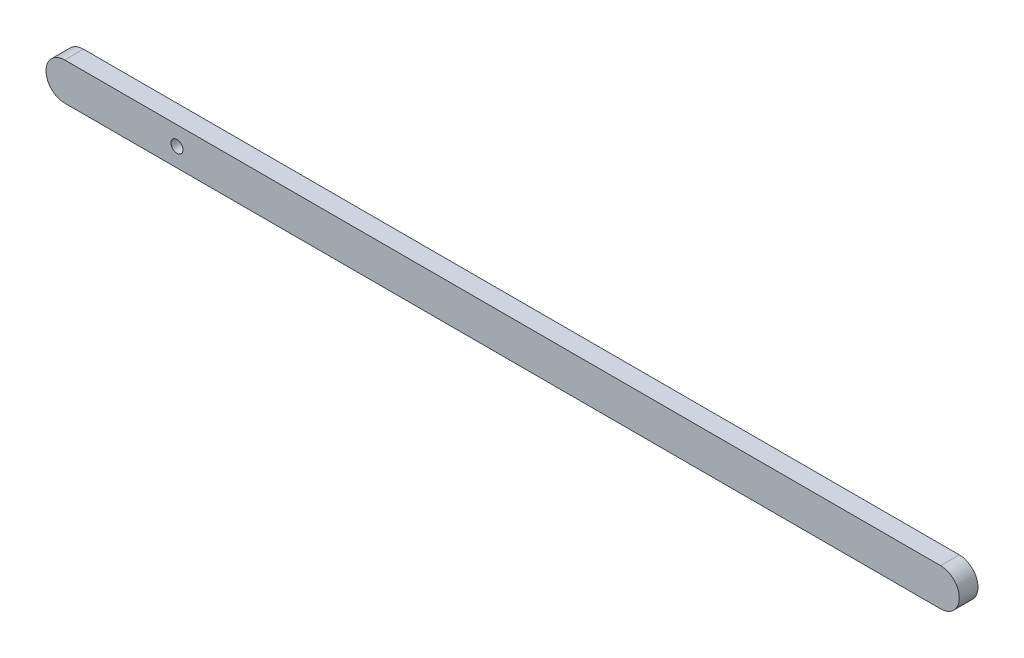
SolidWorks part; units mm, degrees
ref_plane "前视基准面" through (0, 0, 0) normal (0, 0, 1) x (1, 0, 0)
ref_plane "上视基准面" through (0, 0, 0) normal (0, 1, 0) x (1, 0, 0)
ref_plane "右视基准面" through (0, 0, 0) normal (1, 0, 0) x (0, 0, -1)
other "Configuration Table"
sketch "草图1" plane through (0, 0, 0) normal (0, 0, 1) x (1, 0, 0)
  line L0 (0, 0) -> (234, 0) construction
  line L1 (0, 5) -> (234, 5)
  line L2 (0, -5) -> (234, -5)
  arc A0 (0, 5) -> (0, -5) centre (0, 0) ccw
  arc A1 (234, -5) -> (234, 5) centre (234, 0) ccw
  circle A2 centre (30, 0) radius 1.6
  point P3 (117, 0)
  dimension "D4" = 3.2
  dimension "D1" = 234
  dimension "D2" = 30
  dimension "D3" = 10
extrude "凸台-拉伸1" add sketch "草图1" along normal blind 5
